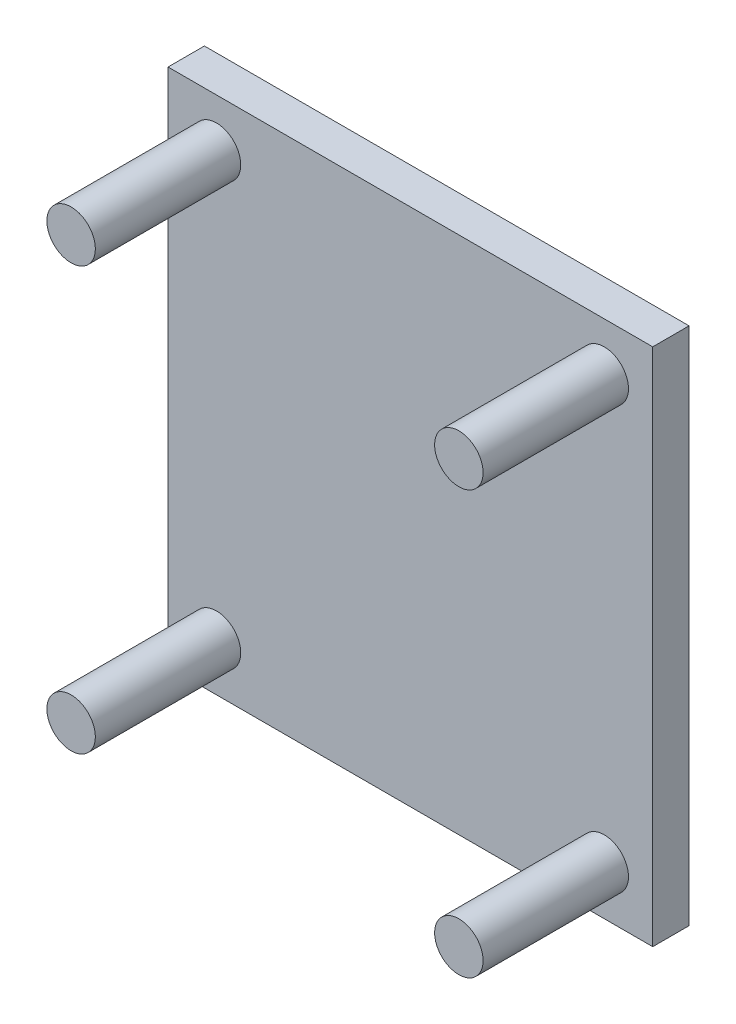
SolidWorks part; units mm, degrees
ref_plane "Спереди" through (0, 0, 0) normal (0, 0, 1) x (1, 0, 0)
ref_plane "Сверху" through (0, 0, 0) normal (0, 1, 0) x (1, 0, 0)
ref_plane "Справа" through (0, 0, 0) normal (1, 0, 0) x (0, 0, -1)
sketch "Эскиз1" plane through (0, 0, 0) normal (0, 0, 1) x (1, 0, 0)
  line L0 (-20, -21.4381) -> (20, -21.4381)
  line L1 (20, -21.4381) -> (20, 21.4381)
  line L2 (20, 21.4381) -> (-20, 21.4381)
  line L3 (-20, 21.4381) -> (-20, -21.4381)
extrude "Former_base" add sketch "Эскиз1" along normal blind 3
sketch "Эскиз2" plane through (0, 0, 0) normal (0, 0, 1) x (1, 0, 0)
  circle A0 centre (-16, -17.4381) radius 2
  circle A1 centre (-16, 17.4381) radius 2
  circle A2 centre (16, -17.4381) radius 2
  circle A3 centre (16, 17.4381) radius 2
extrude "Former_posts" add sketch "Эскиз2" along normal blind 12 from offset 3
